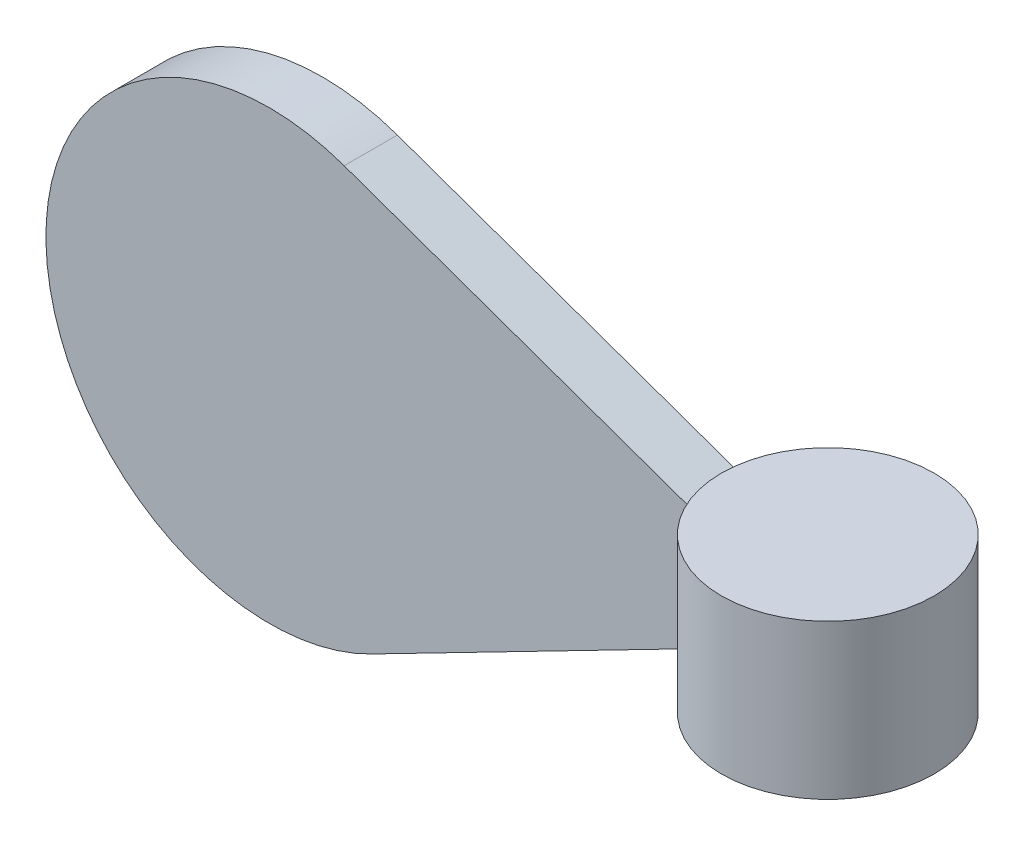
SolidWorks part; units mm, degrees
material "A286 铁基超合金"
ref_plane "前视基准面" through (0, 0, 0) normal (0, 0, 1) x (1, 0, 0)
ref_plane "上视基准面" through (0, 0, 0) normal (0, 1, 0) x (1, 0, 0)
ref_plane "右视基准面" through (0, 0, 0) normal (1, 0, 0) x (0, 0, -1)
other "Configuration Table"
sketch "草图1" plane through (0, 0, 0) normal (0, 0, 1) x (1, 0, 0)
  circle A0 centre (0, 0) radius 42
  dimension "D1" = 84
extrude "凸台-拉伸1" add sketch "草图1" along normal blind 20
sketch "草图2" plane through (0, 0, 20) normal (0, 0, 1) x (1, 0, 0)
  line L0 (0, 0) -> (150.9371, 0) construction
  line L1 (100, 22.7173) -> (100, -21.6499) construction
  line L2 (100, 20) -> (100, 15)
  line L3 (80, 20) -> (100, 20)
  line L4 (80, 20) -> (80, -9)
  line L8 (80, -9) -> (88, -9)
  arc A1 (100, 15) -> (88, -9) centre (100, 0) ccw
  dimension "D2" = 30
  dimension "D1" = 100
  dimension "D3" = 20
  dimension "D4" = 20
  dimension "D5" = 9
revolve "旋转1" add sketch "草图2" angle 360 about L1
sketch "草图3" plane through (0, 0, 20) normal (0, 0, 1) x (1, 0, 0)
  line L0 (14.0695, 39.5734) -> (86, 14)
  line L1 (19.2087, -37.35) -> (86, -3)
  line L4 (86, 14) -> (86, -3)
  circle A1 centre (0, 0) radius 42
  arc A2 (14.0695, 39.5734) -> (19.2087, -37.35) centre (0, 0) ccw
  dimension "D2" = 86
  dimension "D3" = 14
  dimension "D4" = 3
  dimension "D1" = 0
extrude "凸台-拉伸2" add sketch "草图3" along normal mid plane 10
sketch "草图4" plane through (0, 0, 0) normal (0, 0, -1) x (-1, 0, 0)
  circle A1 centre (0, 0) radius 42
  circle A2 centre (0, 0) radius 42
  dimension "D1" = 0
extrude "切除-拉伸1" cut sketch "草图4" against normal up to surface (15 mm away) up to face at (54.954, 3.5149, 15)
